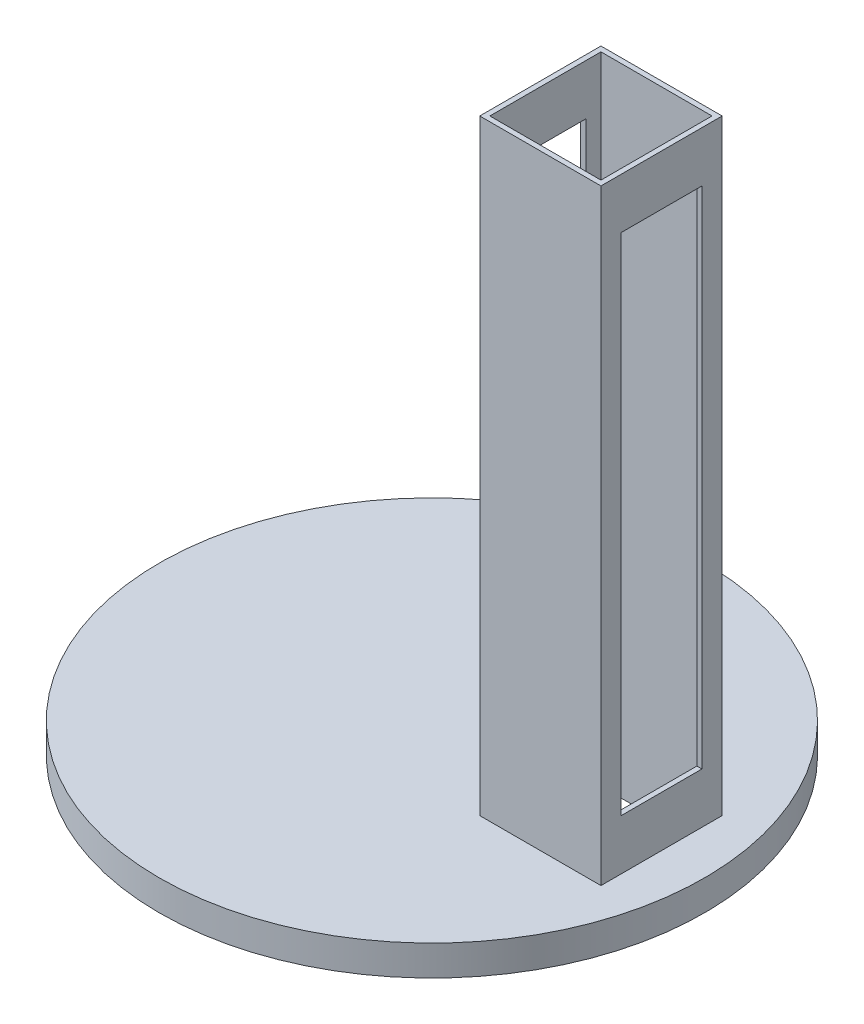
SolidWorks part; units mm, degrees
ref_plane "Front Plane" through (0, 0, 0) normal (0, 0, 1) x (1, 0, 0)
ref_plane "Top Plane" through (0, 0, 0) normal (0, 1, 0) x (1, 0, 0)
ref_plane "Right Plane" through (0, 0, 0) normal (1, 0, 0) x (0, 0, -1)
sketch "Sketch1" plane through (0, 0, 0) normal (0, 1, 0) x (1, 0, 0)
  circle A0 centre (0, 0) radius 27
  dimension "D1" = 54
extrude "Boss-Extrude2" add sketch "Sketch1" along normal blind 3 contours A0
sketch "Sketch3" plane through (0, 3, 0) normal (0, 1, 0) x (1, 0, 0)
  line L1 (22.0279, -5.2916) -> (11.0279, -5.2916)
  line L2 (22.0279, -5.2916) -> (22.0279, 5.7084)
  line L3 (22.0279, 5.7084) -> (11.0279, 5.7084)
  line L4 (11.0279, -5.2916) -> (11.0279, 5.7084)
  line L5 (22.0279, -5.2916) -> (11.0279, 5.7084) construction
  line L6 (22.0279, 5.7084) -> (11.0279, -5.2916) construction
  line L7 (22.5279, 6.2084) -> (10.5279, 6.2084)
  line L8 (22.5279, 6.2084) -> (22.5279, -5.7916)
  line L9 (22.5279, -5.7916) -> (10.5279, -5.7916)
  line L10 (10.5279, 6.2084) -> (10.5279, -5.7916)
  line L11 (22.5279, 6.2084) -> (10.5279, -5.7916) construction
  line L12 (22.5279, -5.7916) -> (10.5279, 6.2084) construction
  circle A0 centre (0, 0) radius 7.5
  point P3 (16.5279, 0.2084)
  point P8 (16.5279, 0.2084)
  dimension "D1" = 15
  dimension "D2" = 11
  dimension "D3" = 11
  dimension "D4" = 12
  dimension "D5" = 12
extrude "Cut-Extrude1" cut sketch "Sketch3" against normal blind 3 contours L2 L1 L4 L3
sketch "Sketch5" plane through (0, 3, 0) normal (0, 1, 0) x (1, 0, 0)
  line L3 (10.5279, 6.2084) -> (22.5279, 6.2084)
  line L4 (10.5279, 6.2084) -> (10.5279, -5.7916)
  line L5 (10.5279, -5.7916) -> (22.5279, -5.7916)
  line L6 (22.5279, 6.2084) -> (22.5279, -5.7916)
  line L9 (11.0279, 5.7084) -> (22.0279, 5.7084)
  line L10 (11.0279, 5.7084) -> (11.0279, -5.2916)
  line L11 (11.0279, -5.2916) -> (22.0279, -5.2916)
  line L12 (22.0279, 5.7084) -> (22.0279, -5.2916)
  point P8 (16.5279, 0.2084)
  point P13 (16.5279, 0.2084)
  dimension "D1" = 12
  dimension "D2" = 12
extrude "Boss-Extrude3" add sketch "Sketch5" along normal blind 60 contours L4 L3 L6 L5 | L10 L9 L12 L11
sketch "Sketch6" plane through (22.5279, 0, 0) normal (1, 0, 0) x (0, 0, -1)
  line L0 (0.2084, 63) -> (0.2084, 53.5584) construction
  line L1 (-3.7916, 58) -> (4.2084, 58)
  line L2 (-3.7916, 58) -> (-3.7916, 8)
  line L3 (-3.7916, 8) -> (4.2084, 8)
  line L4 (4.2084, 58) -> (4.2084, 8)
  line L5 (6.2084, 63) -> (-5.7916, 63) construction
  line L6 (6.2084, 33) -> (-9.4377, 33) construction
  line L7 (6.2084, 63) -> (6.2084, 3) construction
  dimension "D1" = 4
  dimension "D2" = 8
  dimension "D3" = 50
  dimension "D4" = 25
extrude "Cut-Extrude2" cut sketch "Sketch6" against normal blind 60 contours L2 L1 L4 L3
